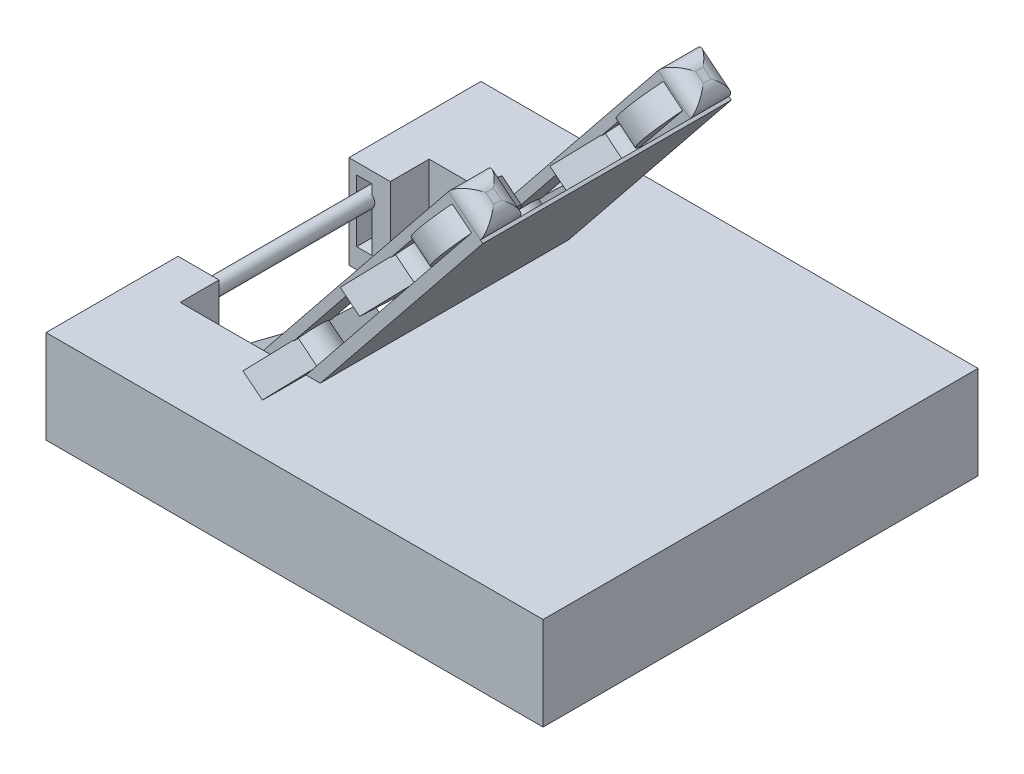
SolidWorks part; units mm, degrees
ref_plane "Front Plane" through (0, 0, 0) normal (0, 0, 1) x (1, 0, 0)
ref_plane "Top Plane" through (0, 0, 0) normal (0, 1, 0) x (1, 0, 0)
ref_plane "Right Plane" through (0, 0, 0) normal (1, 0, 0) x (0, 0, -1)
sketch "Sketch1" plane through (0, 0, 0) normal (0, 1, 0) x (1, 0, 0)
  line L1 (0, 0) -> (812.8, 0)
  line L2 (0, 0) -> (0, -711.2)
  line L3 (0, -711.2) -> (812.8, -711.2)
  line L4 (812.8, 0) -> (812.8, -711.2)
  dimension "D1" = 711.2
  dimension "D2" = 812.8
extrude "Boss-Extrude1" add sketch "Sketch1" along normal blind 152.4
ref_plane "Plane1" through (0, 0, 558.8) normal (0, 0, 1) x (1, 0, 0)
ref_plane "Plane2" through (0, 0, 152.4) normal (0, 0, -1) x (-1, 0, 0)
sketch "Sketch2" plane through (0, 0, 152.4) normal (0, 0, -1) x (-1, 0, 0)
  line L0 (0, 0) -> (-203.2, 152.4)
  line L1 (-812.8, 152.4) -> (0, 152.4) construction
  line L2 (-203.2, 152.4) -> (0, 152.4)
  line L3 (0, 152.4) -> (0, 0)
  dimension "D1" = 254
extrude "Cut-Extrude1" cut sketch "Sketch2" against normal blind 406.4 contours L0 L2 L3
sketch "Sketch5" plane through (0, 0, 558.8) normal (0, 0, 1) x (1, 0, 0)
  line L0 (203.2, 152.4) -> (521.4951, 548.3195)
  line L1 (521.4951, 548.3195) -> (554.1242, 522.0877)
  line L2 (554.1242, 522.0877) -> (256.9178, 152.4)
  line L3 (0, 152.4) -> (812.8, 152.4) construction
  line L4 (256.9178, 152.4) -> (203.2, 152.4)
  dimension "D1" = 508
extrude "Boss-Extrude2" add sketch "Sketch5" against normal blind 406.4
sketch "Sketch6" plane through (472.489, 587.7174, 0) normal (0.6266, 0.7794, 0) x (0.7794, -0.6266, 0)
  line L0 (62.8792, -152.4) -> (62.8792, -558.8) construction
  line L1 (62.8792, -203.2) -> (104.7452, -203.2)
  line L2 (62.8792, -203.2) -> (62.8792, -508)
  line L3 (62.8792, -508) -> (104.7452, -508)
  line L4 (104.7452, -203.2) -> (104.7452, -508)
  line L5 (104.7452, -152.4) -> (104.7452, -558.8) construction
  line L6 (-83.82, -558.8) -> (83.82, -558.8) construction
  dimension "D1" = 304.8
  dimension "D2" = 50.8
extrude "Cut-Extrude3" cut sketch "Sketch6" against normal blind 508
sketch "Sketch8" plane through (81.6352, -65.6297, 0) normal (0.7794, -0.6266, 0) x (0, 0, -1)
  line L0 (-508, 754.0939) -> (-508, 279.7516) construction
  line L1 (-558.8, 754.0939) -> (-508, 754.0939)
  line L2 (-558.8, 754.0939) -> (-558.8, 246.0939)
  line L3 (-558.8, 246.0939) -> (-508, 246.0939)
  line L4 (-508, 754.0939) -> (-508, 246.0939)
  dimension "D1" = 508
extrude "Boss-Extrude3" add sketch "Sketch8" along normal blind 25.4
sketch "Sketch9" plane through (81.6352, -65.6297, 0) normal (0.7794, -0.6266, 0) x (0, 0, -1)
  line L0 (-152.4, 279.7516) -> (-152.4, 754.0939) construction
  line L1 (-203.2, 754.0939) -> (-152.4, 754.0939)
  line L2 (-203.2, 754.0939) -> (-203.2, 246.0939)
  line L3 (-203.2, 246.0939) -> (-152.4, 246.0939)
  line L4 (-152.4, 754.0939) -> (-152.4, 246.0939)
  dimension "D1" = 508
extrude "Boss-Extrude4" add sketch "Sketch9" along normal blind 25.4
sketch "Sketch10" plane through (0, 0, 203.2) normal (0, 0, 1) x (1, 0, 0)
  line L0 (203.2, 152.4) -> (521.4951, 548.3195)
  line L1 (521.4951, 548.3195) -> (573.9201, 506.1729)
  line L2 (573.9201, 506.1729) -> (289.5083, 152.4)
  line L3 (289.5083, 152.4) -> (256.9178, 152.4)
  line L4 (256.9178, 152.4) -> (235.8291, 126.1682)
  line L5 (235.8291, 126.1682) -> (203.2, 152.4)
extrude "Boss-Extrude5" add sketch "Sketch10" along normal blind 12.7
sketch "Sketch11" plane through (0, 0, 508) normal (0, 0, -1) x (-1, 0, 0)
  line L0 (-573.9201, 506.1729) -> (-289.5083, 152.4)
  line L1 (-289.5083, 152.4) -> (-256.9178, 152.4)
  line L2 (-256.9178, 152.4) -> (-235.8291, 126.1682)
  line L3 (-235.8291, 126.1682) -> (-203.2, 152.4)
  line L4 (-203.2, 152.4) -> (-521.4951, 548.3195)
  line L5 (-521.4951, 548.3195) -> (-573.9201, 506.1729)
extrude "Boss-Extrude6" add sketch "Sketch11" along normal blind 12.7
sketch "Sketch12" plane through (0, 0, 152.4) normal (0, 0, -1) x (-1, 0, 0)
  line L0 (-272.89, 152.4) -> (-543.4408, 488.9315)
  line L1 (-812.8, 152.4) -> (0, 152.4) construction
  line L2 (-543.4408, 488.9315) -> (-512.5781, 513.7433)
  line L3 (-512.5781, 513.7433) -> (-222.0802, 152.4)
  line L4 (-203.2, 152.4) -> (-289.5083, 152.4) construction
  line L5 (-222.0802, 152.4) -> (-272.89, 152.4)
  dimension "D1" = 431.8
extrude "Cut-Extrude4" cut sketch "Sketch12" against normal up to vertex
fillet "Fillet1" radius 25.4 8 edges at (547.7076, 527.2462, 495.3) (547.7076, 527.2462, 558.8) (547.7076, 527.2462, 215.9) (547.7076, 527.2462, 152.4) (521.4951, 548.3195, 184.15) (573.9201, 506.1729, 184.15) (521.4951, 548.3195, 527.05) (573.9201, 506.1729, 527.05)
sketch "Sketch16" plane through (101.4312, -81.5445, 0) normal (0.7794, -0.6266, 0) x (0, 0, -1)
  line L0 (-152.4, -83.82) -> (-152.4, 83.82) construction
  line L1 (-558.8, 728.6939) -> (-152.4, 728.6939)
  line L2 (-558.8, 728.6939) -> (-558.8, 296.8939)
  line L3 (-558.8, 296.8939) -> (-152.4, 296.8939)
  line L4 (-152.4, 728.6939) -> (-152.4, 296.8939)
  dimension "D1" = 431.8
extrude "Boss-Extrude8" add sketch "Sketch16" along normal blind 5.08
sketch "Sketch18" plane through (154.1939, 191.7979, 0) normal (0.6266, 0.7794, 0) x (0.7794, -0.6266, 0)
  line L0 (62.8792, -215.9) -> (0, -215.9)
  line L1 (62.8792, -215.9) -> (104.7452, -215.9)
  line L3 (62.8792, -495.3) -> (104.7452, -495.3)
  line L5 (0, -215.9) -> (0, -495.3)
  line L6 (0, -495.3) -> (62.8792, -495.3)
  line L7 (104.7452, -215.9) -> (130.1452, -215.9)
  line L8 (130.1452, -215.9) -> (130.1452, -495.3)
  line L9 (130.1452, -495.3) -> (104.7452, -495.3)
extrude "Cut-Extrude5" cut sketch "Sketch18" against normal blind 508 contours L5 L6 L3 L9 L8 L7 L1 L0
sketch "Sketch20" plane through (154.1939, 191.7979, 0) normal (-0.6266, -0.7794, 0) x (-0.7794, 0.6266, 0)
  line L1 (-104.7452, -495.3) -> (-130.1452, -495.3)
  line L2 (-104.7452, -495.3) -> (-104.7452, -215.9)
  line L3 (-104.7452, -215.9) -> (-130.1452, -215.9)
  line L4 (-130.1452, -495.3) -> (-130.1452, -215.9)
extrude "Cut-Extrude6" cut sketch "Sketch20" against normal blind 508
sketch "Sketch21" plane through (91.3369, -73.4293, 0) normal (-0.7794, 0.6266, 0) x (0, 0, 1)
  line L4 (209.3976, 562.2935) -> (289.1019, 546.3666)
  line L5 (289.1019, 546.3666) -> (210.5655, 525.427)
  line L6 (158.9024, 523.7904) -> (79.9352, 543.0419)
  line L7 (79.9352, 543.0419) -> (158.9024, 562.2935)
  line L8 (289.1019, 292.3666) -> (210.5655, 271.427)
  line L9 (209.3976, 308.2935) -> (289.1019, 292.3666)
  line L10 (79.9352, 289.0419) -> (158.9024, 308.2935)
  line L11 (158.9024, 269.7904) -> (79.9352, 289.0419)
  line L12 (632.0019, 292.3666) -> (553.4655, 271.427)
  line L13 (552.2976, 308.2935) -> (632.0019, 292.3666)
  line L14 (501.8024, 269.7904) -> (422.8352, 289.0419)
  line L15 (422.8352, 289.0419) -> (501.8024, 308.2935)
  line L16 (501.8024, 523.7904) -> (422.8352, 543.0419)
  line L17 (632.0019, 546.3666) -> (553.4655, 525.427)
  line L18 (552.2976, 562.2935) -> (632.0019, 546.3666)
  line L19 (422.8352, 543.0419) -> (501.8024, 562.2935)
  arc A0 (158.9024, 523.7904) -> (210.5655, 525.427) centre (184.15, 543.0419) ccw
  arc A1 (209.3976, 562.2935) -> (158.9024, 562.2935) centre (184.15, 543.0419) ccw
  arc A2 (158.9024, 269.7904) -> (210.5655, 271.427) centre (184.15, 289.0419) ccw
  arc A3 (209.3976, 308.2935) -> (158.9024, 308.2935) centre (184.15, 289.0419) ccw
  arc A4 (501.8024, 269.7904) -> (553.4655, 271.427) centre (527.05, 289.0419) ccw
  arc A5 (552.2976, 308.2935) -> (501.8024, 308.2935) centre (527.05, 289.0419) ccw
  arc A6 (501.8024, 523.7904) -> (553.4655, 525.427) centre (527.05, 543.0419) ccw
  arc A7 (552.2976, 562.2935) -> (501.8024, 562.2935) centre (527.05, 543.0419) ccw
  dimension "D1" = 2
  dimension "D2" = 2
  dimension "D5" = 81.28
  dimension "D6" = 81.28
  dimension "D7" = 81.28
  dimension "D8" = 81.28
extrude "Boss-Extrude9" add sketch "Sketch21" along normal blind 40.64
sketch "Sketch22" plane through (91.3369, -73.4293, 0) normal (-0.7794, 0.6266, 0) x (0, 0, 1)
  circle A0 centre (184.15, 670.4976) radius 63.5
  circle A1 centre (519.43, 670.4976) radius 63.5
  dimension "D1" = 127
  dimension "D2" = 2
extrude "Boss-Extrude10" add sketch "Sketch22" along normal blind 40.64
sketch "Sketch23" plane through (0, 0, 215.9) normal (0, 0, 1) x (1, 0, 0)
  circle A0 centre (203.2, 12.7) radius 38.1
  dimension "D1" = 76.2
  dimension "D2" = 203.2
  dimension "D3" = 139.7
extrude "Cut-Extrude7" cut sketch "Sketch23" along normal blind 279.4
sketch "Sketch24" plane through (0, 0, 0) normal (-1, 0, 0) x (0, 0, 1)
  line L1 (215.9, 0) -> (495.3, 0)
  line L2 (215.9, 0) -> (215.9, 50.5426)
  line L3 (215.9, 50.5426) -> (495.3, 50.5426)
  line L4 (495.3, 0) -> (495.3, 50.5426)
extrude "Cut-Extrude8" cut sketch "Sketch24" against normal blind 182.88
sketch "Sketch25" plane through (0, 0, 215.9) normal (0, 0, 1) x (1, 0, 0)
  circle A0 centre (203.2, 12.7) radius 38.1
extrude "Boss-Extrude11" add sketch "Sketch25" along normal blind 279.4
sketch "Sketch26" plane through (0, 0, 215.9) normal (0, 0, 1) x (1, 0, 0)
  line L0 (0, 0) -> (0, 50.8)
  line L1 (0, 152.4) -> (0, 0) construction
  line L2 (0, 50.8) -> (67.7333, 50.8)
  line L3 (0, 0) -> (203.2, 152.4) construction
  line L4 (67.7333, 50.8) -> (0, 0)
  dimension "D1" = 50.8
extrude "Boss-Extrude12" add sketch "Sketch26" against normal blind 63.5 contours L2 L4 L0
sketch "Sketch30" plane through (0, 0, 495.3) normal (0, 0, -1) x (-1, 0, 0)
  line L0 (0, 0) -> (0, 50.8)
  line L1 (0, 50.8) -> (-67.7333, 50.8)
  line L2 (-203.2, 152.4) -> (0, 0) construction
  line L3 (-67.7333, 50.8) -> (0, 0)
  dimension "D1" = 50.8
extrude "Boss-Extrude14" add sketch "Sketch30" against normal blind 63.5 contours L0 L1 L3
sketch "Sketch32" plane through (0, 50.8, 0) normal (0, 1, 0) x (1, 0, 0)
  line L0 (-83.82, -558.8) -> (83.82, -558.8) construction
  line L1 (0, -495.3) -> (67.0497, -495.3)
  line L2 (0, -495.3) -> (0, -558.8)
  line L3 (0, -558.8) -> (67.0497, -558.8)
  line L4 (67.0497, -495.3) -> (67.0497, -558.8)
  line L5 (83.82, -152.4) -> (-83.82, -152.4) construction
  line L6 (0, -215.9) -> (67.7333, -215.9)
  line L7 (0, -215.9) -> (0, -152.4)
  line L8 (0, -152.4) -> (67.7333, -152.4)
  line L9 (67.7333, -215.9) -> (67.7333, -152.4)
  line L10 (67.7333, -152.4) -> (67.7333, -215.9) construction
extrude "Boss-Extrude15" add sketch "Sketch32" along normal blind 101.6
sketch "Sketch33" plane through (0, 0, 215.9) normal (0, 0, 1) x (1, 0, 0)
  line L0 (0, 0) -> (0, 152.4) construction
  line L1 (12.7, 134.2251) -> (38.1, 134.2251)
  line L2 (12.7, 134.2251) -> (12.7, 32.6251)
  line L3 (12.7, 32.6251) -> (38.1, 32.6251)
  line L4 (38.1, 134.2251) -> (38.1, 32.6251)
  dimension "D1" = 12.7
  dimension "D2" = 25.4
  dimension "D3" = 101.6
extrude "Cut-Extrude9" cut sketch "Sketch33" against normal blind 25.4
sketch "Sketch34" plane through (0, 0, 215.9) normal (0, 0, 1) x (1, 0, 0)
  line L5 (12.7, 134.2251) -> (38.1, 134.2251)
  line L6 (12.7, 134.2251) -> (12.7, 32.6251)
  line L7 (12.7, 32.6251) -> (38.1, 32.6251)
  line L8 (38.1, 134.2251) -> (38.1, 32.6251)
extrude "Cut-Extrude11" cut sketch "Sketch34" along normal blind 304.8 contours L6 L7 L8 L5
sketch "Sketch36" plane through (0, 0, 190.5) normal (0, 0, 1) x (1, 0, 0)
  line L0 (67.7333, 152.4) -> (67.7333, 50.8) construction
  circle A0 centre (29.6333, 108.8251) radius 12.7
  dimension "D1" = 25.4
  dimension "D2" = 38.1
  dimension "D3" = 25.4
extrude "Boss-Extrude16" add sketch "Sketch36" along normal blind 317.5
ref_plane "Plane3" through (0, 0, 266.7) normal (0, 0, 1) x (1, 0, 0)
